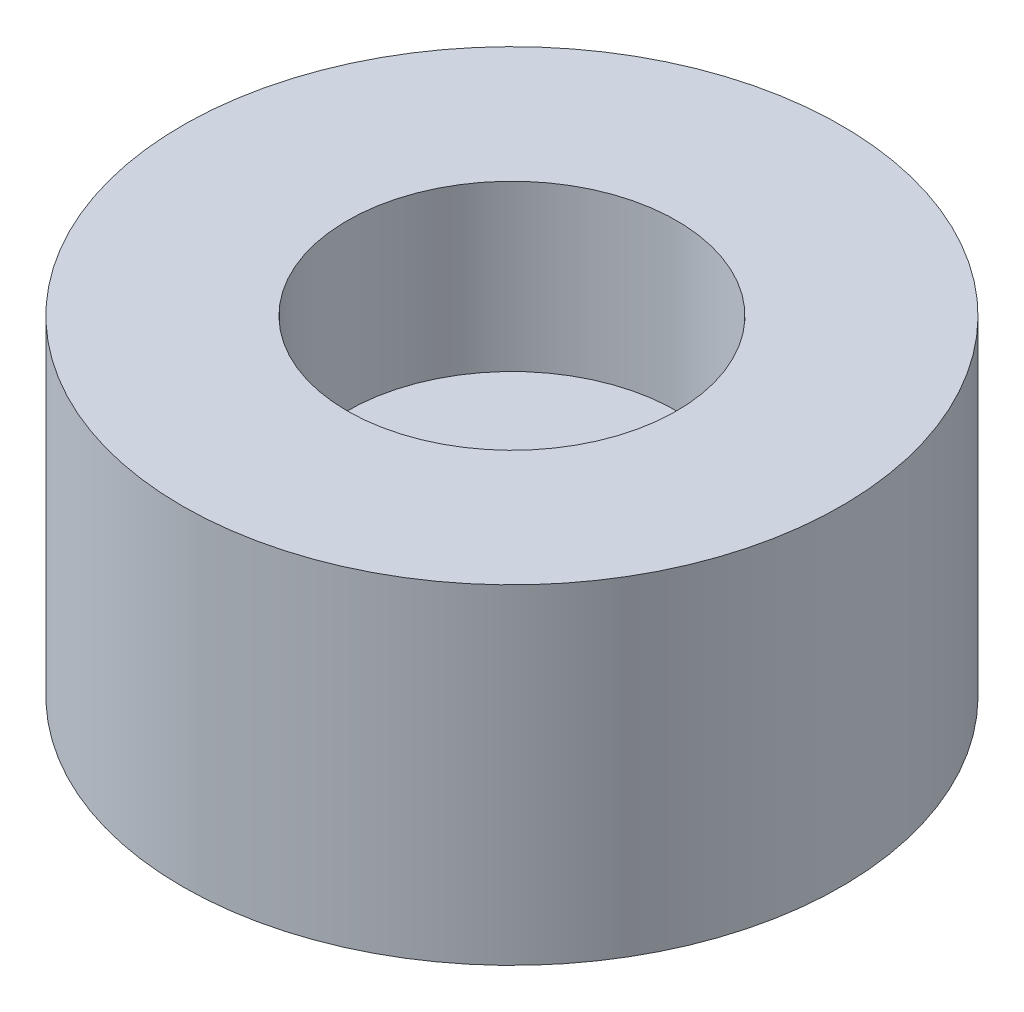
SolidWorks part; units mm, degrees
ref_plane "Front Plane" through (0, 0, 0) normal (0, 0, 1) x (1, 0, 0)
ref_plane "Top Plane" through (0, 0, 0) normal (0, 1, 0) x (1, 0, 0)
ref_plane "Right Plane" through (0, 0, 0) normal (1, 0, 0) x (0, 0, -1)
sketch "Sketch1" plane through (0, 0, 0) normal (0, 1, 0) x (1, 0, 0)
  circle A0 centre (0, 0) radius 5.08
  dimension "D1" = 10.16
extrude "Boss-Extrude1" add sketch "Sketch1" along normal blind 5.08
sketch "Sketch2" plane through (0, 5.08, 0) normal (0, 1, 0) x (1, 0, 0)
  circle A0 centre (0, 0) radius 2.54
  dimension "D1" = 5.08
extrude "Cut-Extrude1" cut sketch "Sketch2" against normal blind 2.54
